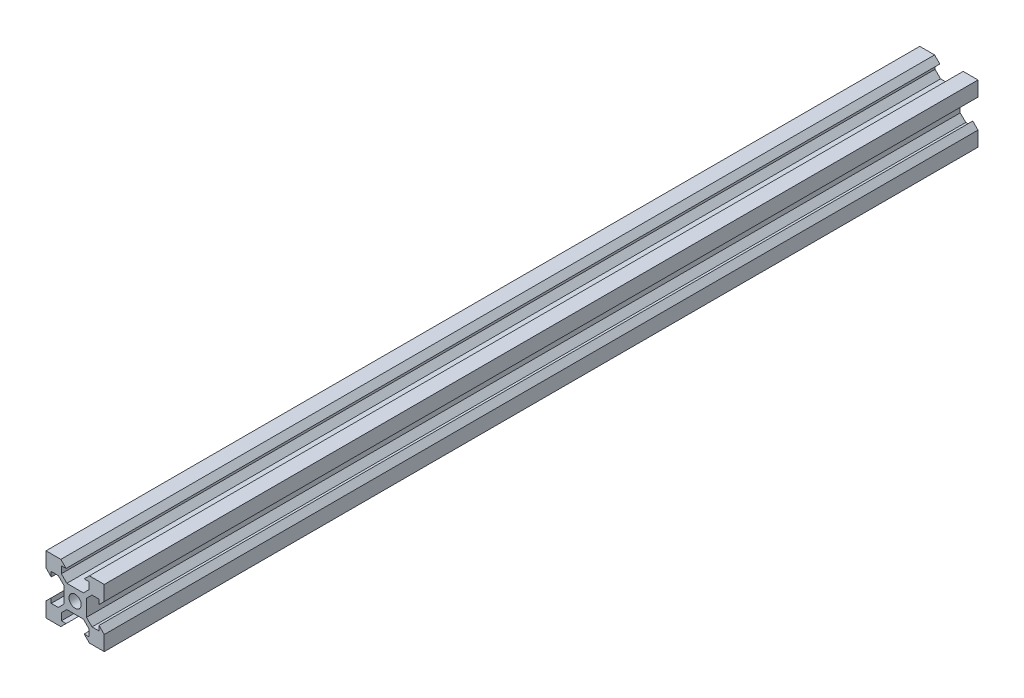
SolidWorks part; units mm, degrees
material "6063-T5"
ref_plane "Front Plane" through (0, 0, 0) normal (0, 0, 1) x (1, 0, 0)
ref_plane "Top Plane" through (0, 0, 0) normal (0, 1, 0) x (1, 0, 0)
ref_plane "Right Plane" through (0, 0, 0) normal (1, 0, 0) x (0, 0, -1)
sketch "Sketch1" plane through (0, 0, 0) normal (0, 0, 1) x (1, 0, 0)
  line L0 (-3.9007, -2.84) -> (-3.9007, 2.84)
  line L1 (-3.9007, 2.84) -> (-5.8007, 4.74)
  line L2 (-5.8007, 4.74) -> (-8.2, 4.74)
  line L3 (-8.2, 4.74) -> (-8.2, 3.1)
  line L4 (-10, 10) -> (-1.4849, 1.4849) construction
  line L5 (0, 3.9007) -> (-2.84, 3.9007)
  line L6 (-2.84, 3.9007) -> (-4.74, 5.8007)
  line L7 (-4.74, 8.2) -> (-3.1, 8.2)
  line L8 (-4.74, 5.8007) -> (-4.74, 8.2)
  line L9 (-3.1, 8.2) -> (-4.9, 10)
  line L10 (-4.9, 10) -> (-10, 10)
  line L11 (-10, 10) -> (-10, 4.9)
  line L12 (-8.2, 3.1) -> (-10, 4.9)
  line L13 (0, 3.9007) -> (0, -3.9007) construction
  line L14 (10, 10) -> (1.4849, 1.4849) construction
  line L15 (8.2, 3.1) -> (10, 4.9)
  line L16 (10, 10) -> (10, 4.9)
  line L17 (4.9, 10) -> (10, 10)
  line L18 (3.1, 8.2) -> (4.9, 10)
  line L19 (4.74, 5.8007) -> (4.74, 8.2)
  line L20 (4.74, 8.2) -> (3.1, 8.2)
  line L21 (2.84, 3.9007) -> (4.74, 5.8007)
  line L22 (8.2, 4.74) -> (8.2, 3.1)
  line L23 (5.8007, 4.74) -> (8.2, 4.74)
  line L24 (3.9007, 2.84) -> (5.8007, 4.74)
  line L25 (2.84, 3.9007) -> (0, 3.9007)
  line L26 (3.9007, 2.84) -> (3.9007, -2.84)
  line L27 (-3.9007, 0) -> (3.9007, 0) construction
  line L28 (10, -10) -> (1.4849, -1.4849) construction
  line L29 (-10, -10) -> (-1.4849, -1.4849) construction
  line L30 (2.84, -3.9007) -> (0, -3.9007)
  line L31 (3.9007, -2.84) -> (5.8007, -4.74)
  line L32 (5.8007, -4.74) -> (8.2, -4.74)
  line L33 (8.2, -4.74) -> (8.2, -3.1)
  line L34 (2.84, -3.9007) -> (4.74, -5.8007)
  line L35 (4.74, -8.2) -> (3.1, -8.2)
  line L36 (4.74, -5.8007) -> (4.74, -8.2)
  line L37 (3.1, -8.2) -> (4.9, -10)
  line L38 (4.9, -10) -> (10, -10)
  line L39 (10, -10) -> (10, -4.9)
  line L40 (8.2, -3.1) -> (10, -4.9)
  line L41 (-8.2, -3.1) -> (-10, -4.9)
  line L42 (-10, -10) -> (-10, -4.9)
  line L43 (-4.9, -10) -> (-10, -10)
  line L44 (-3.1, -8.2) -> (-4.9, -10)
  line L45 (-4.74, -5.8007) -> (-4.74, -8.2)
  line L46 (-4.74, -8.2) -> (-3.1, -8.2)
  line L47 (-2.84, -3.9007) -> (-4.74, -5.8007)
  line L48 (0, -3.9007) -> (-2.84, -3.9007)
  line L49 (-8.2, -4.74) -> (-8.2, -3.1)
  line L50 (-5.8007, -4.74) -> (-8.2, -4.74)
  line L51 (-3.9007, -2.84) -> (-5.8007, -4.74)
  circle A0 centre (0, 0) radius 2.1
  point P10 (-4.8507, 3.79)
  dimension "D1" = 4.2
  dimension "D2" = 5.68
  dimension "D3" = 1.64
  dimension "D4" = 6.2
  dimension "D5" = 0.75
  dimension "D6" = 10
  dimension "D7" = 90
  dimension "D8" = 1.8
extrude "Boss-Extrude1" add sketch "Sketch1" along normal mid plane 300
